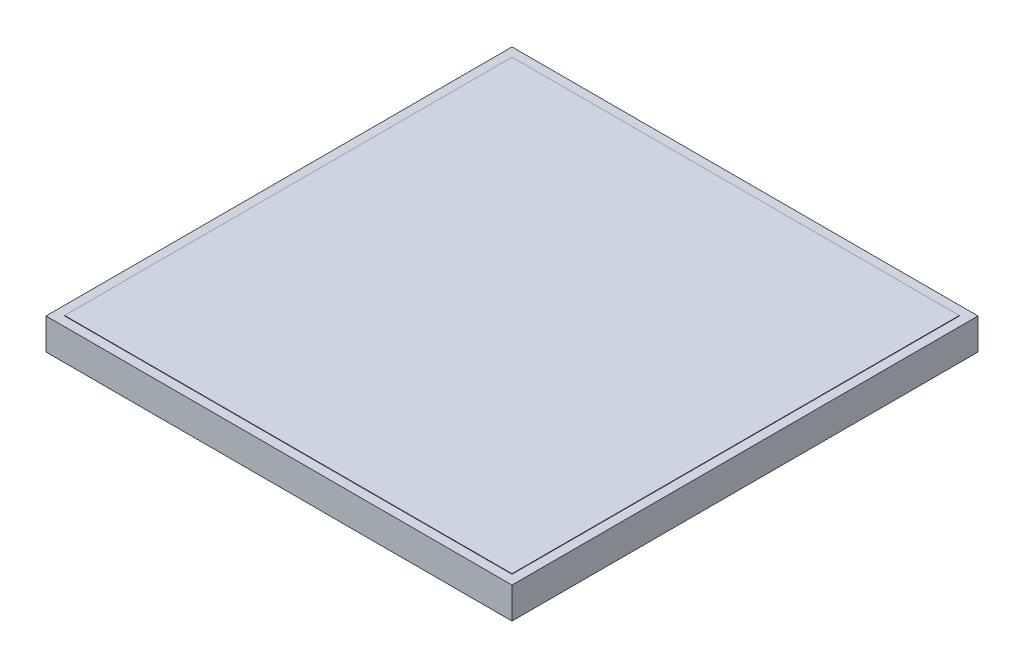
SolidWorks part; units mm, degrees
ref_plane "Front Plane" through (0, 0, 0) normal (0, 0, 1) x (1, 0, 0)
ref_plane "Top Plane" through (0, 0, 0) normal (0, 1, 0) x (1, 0, 0)
ref_plane "Right Plane" through (0, 0, 0) normal (1, 0, 0) x (0, 0, -1)
sketch "Sketch1" plane through (0, 0, 0) normal (0, 1, 0) x (1, 0, 0)
  line L1 (-5, 5) -> (5, 5)
  line L2 (-5, 5) -> (-5, -5)
  line L3 (-5, -5) -> (5, -5)
  line L4 (5, 5) -> (5, -5)
  line L5 (-5, 5) -> (5, -5) construction
  line L6 (-5, -5) -> (5, 5) construction
  point P0 (0, 0)
  dimension "D1" = 10
extrude "Boss-Extrude1" add sketch "Sketch1" along normal blind 0.68
sketch "Sketch2" plane through (0, 0.68, 0) normal (0, 1, 0) x (1, 0, 0)
  line L1 (4.8, -4.8) -> (-4.8, -4.8)
  line L2 (4.8, -4.8) -> (4.8, 4.8)
  line L3 (4.8, 4.8) -> (-4.8, 4.8)
  line L4 (-4.8, -4.8) -> (-4.8, 4.8)
  line L5 (4.8, -4.8) -> (-4.8, 4.8) construction
  line L6 (4.8, 4.8) -> (-4.8, -4.8) construction
  line L7 (5, -5) -> (-5, -5)
  line L8 (5, -5) -> (5, 5)
  line L9 (5, 5) -> (-5, 5)
  line L10 (-5, -5) -> (-5, 5)
  line L11 (5, -5) -> (-5, 5) construction
  line L12 (5, 5) -> (-5, -5) construction
  point P0 (0, 0)
  point P6 (0, 0)
  dimension "D1" = 9.6
extrude "Cut-Extrude1" cut sketch "Sketch2" against normal blind 0.01
